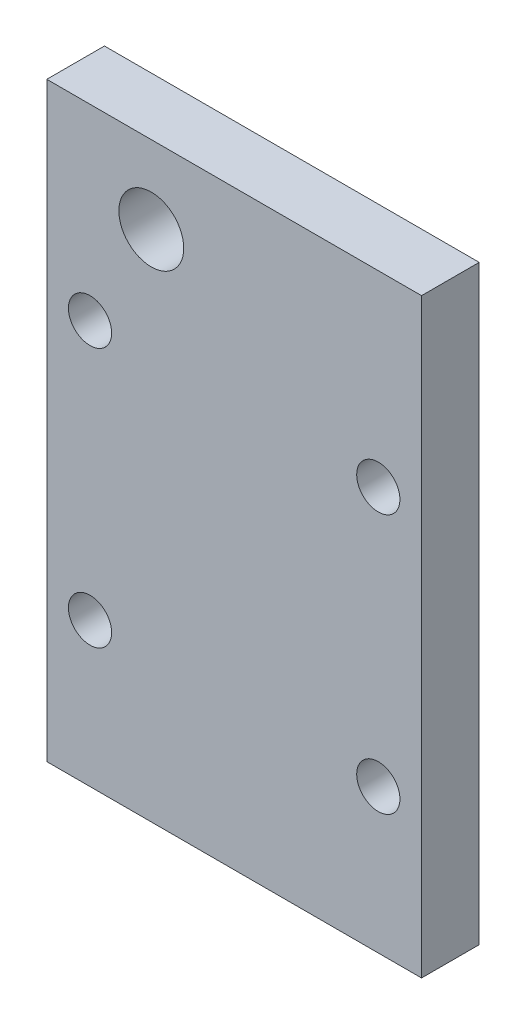
SolidWorks part; units mm, degrees
ref_plane "Front Plane" through (0, 0, 0) normal (0, 0, 1) x (1, 0, 0)
ref_plane "Top Plane" through (0, 0, 0) normal (0, 1, 0) x (1, 0, 0)
ref_plane "Right Plane" through (0, 0, 0) normal (1, 0, 0) x (0, 0, -1)
sketch "Sketch1" plane through (0, 0, 0) normal (0, 0, 1) x (1, 0, 0)
  line L8 (0, 0) -> (0, 41) construction
  line L9 (0, 41) -> (3.95, 41) construction
  line L10 (3.95, 41) -> (3.95, 31) construction
  line L11 (3.95, 31) -> (10.3, 31) construction
  line L12 (10.3, 31) -> (10.3, 9) construction
  line L13 (10.3, 9) -> (8.55, 9) construction
  line L14 (8.55, 9) -> (8.55, 4) construction
  line L15 (8.55, 4) -> (13, 4) construction
  line L16 (13, 4) -> (13, 0) construction
  line L17 (13, 0) -> (0, 0) construction
  line L18 (0, 0) -> (0, 41)
  line L19 (0, 41) -> (26, 41)
  line L20 (26, 41) -> (26, 0)
  line L21 (26, 0) -> (0, 0)
  line L22 (3, 41) -> (3, 0) construction
  line L23 (13, 41) -> (13, 0) construction
  circle A0 centre (7.25, 35.6) radius 2.25
  circle A1 centre (3, 28) radius 1.5
  circle A2 centre (3, 10) radius 1.5
  circle A3 centre (23, 10) radius 1.5
  circle A4 centre (23, 28) radius 1.5
  dimension "D12" = 4.5
  dimension "D11" = 5.75
  dimension "D13" = 3
  dimension "D15" = 10
  dimension "D1" = 10
  dimension "D2" = 41
  dimension "D3" = 4
  dimension "D4" = 10.3
  dimension "D5" = 13
  dimension "D6" = 9.05
  dimension "D7" = 5
  dimension "D8" = 1.75
  dimension "D9" = 26
  dimension "D10" = 5.4
  dimension "D14" = 3
  dimension "D16" = 13
extrude "Boss-Extrude1" add sketch "Sketch1" along normal blind 4
